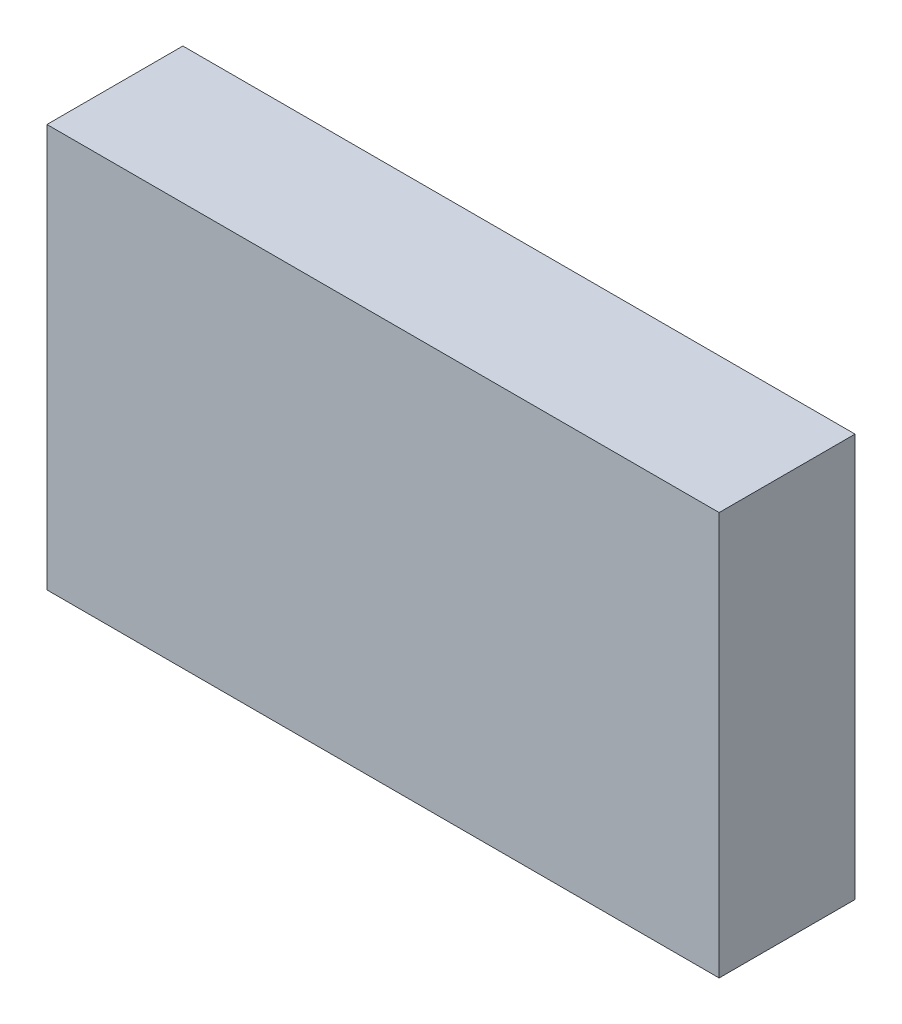
SolidWorks part; units mm, degrees
ref_plane "Front Plane" through (0, 0, 0) normal (0, 0, 1) x (1, 0, 0)
ref_plane "Top Plane" through (0, 0, 0) normal (0, 1, 0) x (1, 0, 0)
ref_plane "Right Plane" through (0, 0, 0) normal (1, 0, 0) x (0, 0, -1)
sketch "Sketch1" plane through (0, 0, 0) normal (0, 0, 1) x (1, 0, 0)
  line L0 (-2.473, 1.483) -> (2.473, 1.483)
  line L1 (2.473, 1.483) -> (2.473, -1.483)
  line L2 (2.473, -1.483) -> (-2.473, -1.483)
  line L3 (-2.473, -1.483) -> (-2.473, 1.483)
extrude "Component_Outline" add sketch "Sketch1" along normal blind 1 separate body
sketch3d "3DSketch1"
  line L0 (0, 0, 0) -> (1, 0, 0)
  line L1 (0, 0, 0) -> (0, 1, 0)
  line L2 (0, 0, 0) -> (0, 0, 1)
  point P0 (0, 0, 0)
